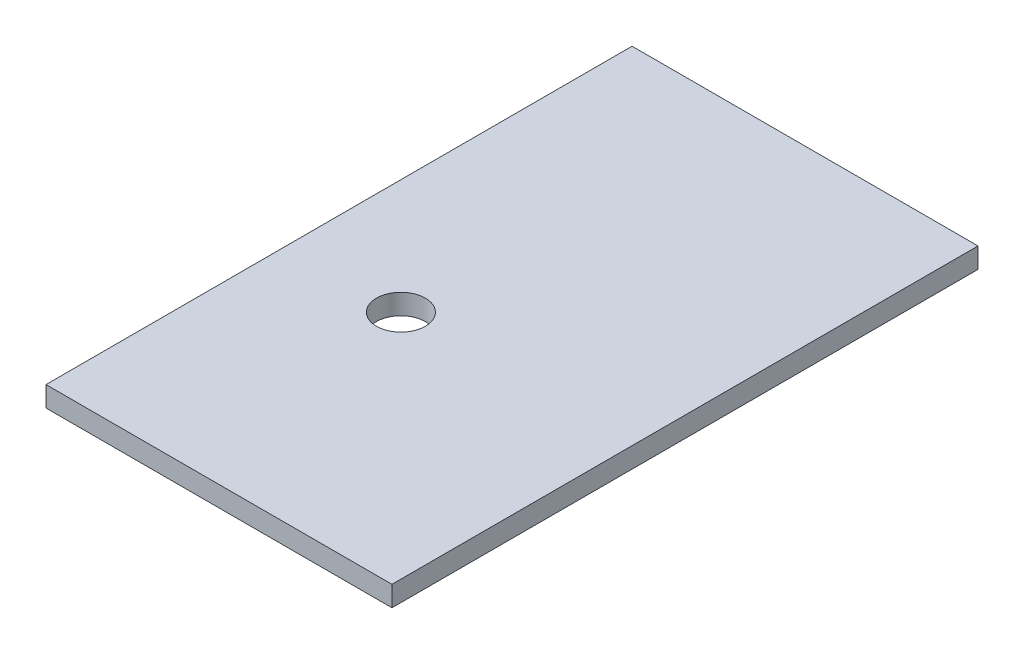
SolidWorks part; units mm, degrees
ref_plane "Front Plane" through (0, 0, 0) normal (0, 0, 1) x (1, 0, 0)
ref_plane "Top Plane" through (0, 0, 0) normal (0, 1, 0) x (1, 0, 0)
ref_plane "Right Plane" through (0, 0, 0) normal (1, 0, 0) x (0, 0, -1)
sketch "Sketch1" plane through (0, 0, 0) normal (0, 1, 0) x (1, 0, 0)
  line L1 (-21.25, 36) -> (21.25, 36)
  line L2 (-21.25, 36) -> (-21.25, -36)
  line L3 (-21.25, -36) -> (21.25, -36)
  line L4 (21.25, 36) -> (21.25, -36)
  circle A2 centre (-7.1496, -6.5) radius 3
  point P4 (0, 36)
  point P6 (-21.25, 0)
  dimension "D3" = 6
  dimension "D1" = 42.5
  dimension "D2" = 72
  dimension "D4" = 6.5
extrude "Boss-Extrude1" add sketch "Sketch1" along normal blind 2.5
equation "\"box_width\"=112"
equation "\"openable_top\"= 72"
equation "\"D1@Sketch1\"=\"wall\"+\"box_width\"-\"openable_top\""
equation "\"wall\"= 2.5"
equation "\"box_length\"=67"
equation "\"D2@Sketch1\"=\"box_length\"+\"wall\"*2"
equation "\"D1@Boss-Extrude1\"=\"wall\""
